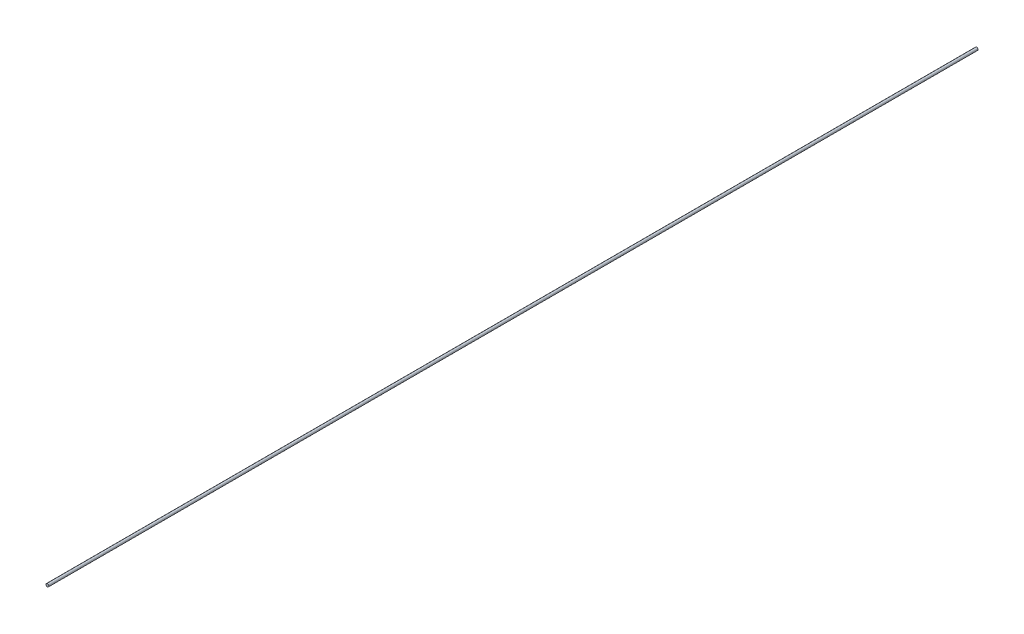
SolidWorks part; units mm, degrees
ref_plane "Front Plane" through (0, 0, 0) normal (0, 0, 1) x (1, 0, 0)
ref_plane "Top Plane" through (0, 0, 0) normal (0, 1, 0) x (1, 0, 0)
ref_plane "Right Plane" through (0, 0, 0) normal (1, 0, 0) x (0, 0, -1)
sketch "Sketch1" plane through (0, 0, 0) normal (0, 0, 1) x (1, 0, 0)
  circle A0 centre (0, 0) radius 1.5
  dimension "D1" = 3
extrude "Boss-Extrude1" add sketch "Sketch1" along normal blind 1000
ref_point "Point2"
ref_point "Point4"
